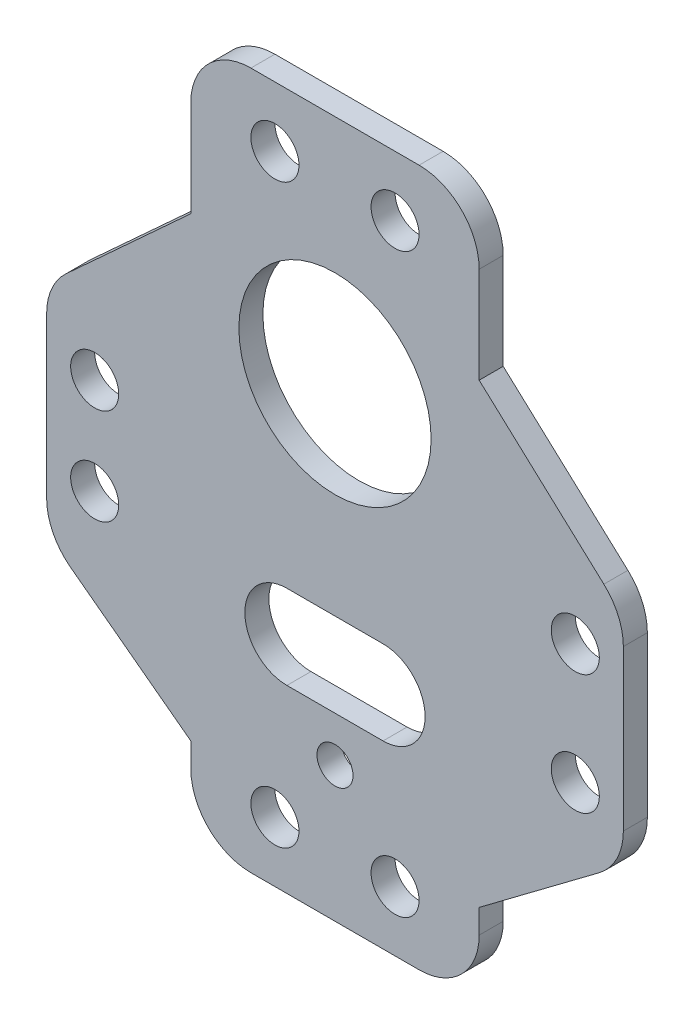
SolidWorks part; units mm, degrees
material "普通碳钢"
ref_plane "前视" through (0, 0, 0) normal (0, 0, 1) x (1, 0, 0)
ref_plane "上视" through (0, 0, 0) normal (0, 1, 0) x (1, 0, 0)
ref_plane "右视" through (0, 0, 0) normal (1, 0, 0) x (0, 0, -1)
sketch "草图1" plane through (0, 0, 0) normal (0, 0, 1) x (1, 0, 0)
  line L0 (0, 0) -> (0, -31) construction
  line L1 (0, -31) -> (-16, -43) construction
  line L2 (-16, -43) -> (-16, -61) construction
  line L3 (-16, -61) -> (4, -71) construction
  line L4 (4, -71) -> (12, -71) construction
  line L5 (0, 0) -> (16, 0) construction
  line L6 (8, 0) -> (8, -71) construction
  line L7 (32, -61) -> (12, -71) construction
  line L8 (32, -43) -> (32, -61) construction
  line L9 (16, -31) -> (32, -43) construction
  line L10 (16, 0) -> (16, -31) construction
  line L11 (4, -6) -> (12, -6) construction
  line L12 (12, -6) -> (12, -31) construction
  line L13 (4, -6) -> (4, -31.3218) construction
  line L14 (4, -58.5) -> (12, -58.5) construction
  line L15 (4, -55) -> (12, -55)
  line L16 (4, -62) -> (12, -62)
  line L17 (-4, -72) -> (20, -72) construction
  line L18 (-12, -48) -> (-12, -56) construction
  line L19 (-16, -52) -> (32, -52) construction
  line L20 (13, -24) -> (3, -24) construction
  line L21 (20, -19) -> (-4, -19)
  line L22 (20, -19) -> (20, -77) construction
  line L23 (20, -77) -> (-4, -77)
  line L24 (-4, -19) -> (-4, -77) construction
  line L25 (3, -24) -> (3, -72) construction
  line L26 (8, -24) -> (8, -72) construction
  line L27 (8, -48) -> (3, -48) construction
  line L28 (32, -43) -> (32, -61)
  line L29 (32, -61) -> (20, -70)
  line L30 (20, -70) -> (20, -77)
  line L31 (13, -70) -> (20, -70) construction
  line L32 (32, -43) -> (20, -32)
  line L33 (20, -32) -> (20, -19)
  line L34 (-4, -70) -> (-4, -77)
  line L35 (-16, -61) -> (-4, -70)
  line L36 (-16, -43) -> (-16, -61)
  line L37 (-16, -43) -> (-4, -32)
  line L38 (-4, -32) -> (-4, -19)
  circle A0 centre (8, -65.75) radius 1.5
  arc A1 (4, -55) -> (4, -62) centre (4, -58.5) ccw
  arc A2 (12, -62) -> (12, -55) centre (12, -58.5) ccw
  circle A3 centre (8, -38.25) radius 8
  circle A4 centre (3, -72) radius 2
  circle A5 centre (13, -72) radius 2
  circle A7 centre (-12, -48) radius 2
  circle A8 centre (-12, -56) radius 2
  circle A9 centre (28, -57) radius 2
  circle A10 centre (28, -47) radius 2
  circle A11 centre (3, -24) radius 2
  circle A12 centre (13, -24) radius 2
  point P20 (8, -58.5)
  point P63 (0, 0)
  point P66 (27.6108, -52)
  dimension "D11" = 16
  dimension "D12" = 3.5
  dimension "D14" = 15
  dimension "D15" = 25
  dimension "D16" = 4
  dimension "D19" = 4
  dimension "D21" = 8
  dimension "D23" = 48
  dimension "D27" = 3
  dimension "D28" = 27.5
  dimension "D29" = 10
  dimension "D1" = 16
  dimension "D2" = 71
  dimension "D3" = 31
  dimension "D4" = 48
  dimension "D5" = 13.75
  dimension "D6" = 12
  dimension "D7" = 8
  dimension "D8" = 6
  dimension "D9" = 8
  dimension "D10" = 25
  dimension "D13" = 9
  dimension "D17" = 58
  dimension "D18" = 10
  dimension "D20" = 4
  dimension "D22" = 10
  dimension "D24" = 24
  dimension "D25" = 13
  dimension "D26" = 18
  dimension "D30" = 5
extrude "凸台-拉伸1" add sketch "草图1" along normal blind 2 contours A3
fillet "圆角1" radius 5 8 edges at (32, -61, 1) (32, -43, 1) (-16, -61, 1) (-16, -43, 1) (-4, -19, 1) (20, -19, 1) (20, -77, 1) (-4, -77, 1)
sketch "草图2" plane through (0, 0, 2) normal (0, 0, 1) x (1, 0, 0)
  line L0 (16, -38.25) -> (0, -38.25)
  line L1 (9.5, -65.75) -> (6.5, -65.75)
  circle A0 centre (8, -38.25) radius 8 construction
  circle A1 centre (8, -65.75) radius 1.5 construction
  circle A2 centre (8, -65.75) radius 1.5 construction
